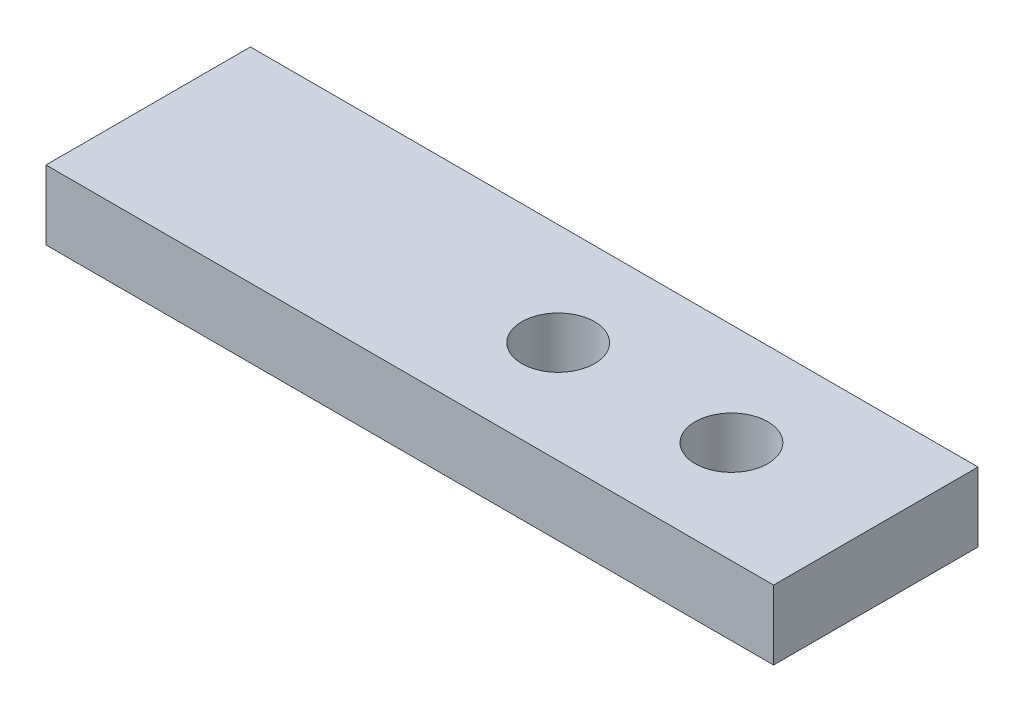
SolidWorks part; units mm, degrees
ref_plane "Front Plane" through (0, 0, 0) normal (0, 0, 1) x (1, 0, 0)
ref_plane "Top Plane" through (0, 0, 0) normal (0, 1, 0) x (1, 0, 0)
ref_plane "Right Plane" through (0, 0, 0) normal (1, 0, 0) x (0, 0, -1)
sketch "Sketch1" plane through (0, 0, 0) normal (0, 1, 0) x (1, 0, 0)
  line L0 (0, 0) -> (16.002, 0) construction
  line L1 (-16.002, 4.4958) -> (16.002, 4.4958)
  line L2 (-16.002, 4.4958) -> (-16.002, -4.4958)
  line L3 (-16.002, -4.4958) -> (16.002, -4.4958)
  line L4 (16.002, 4.4958) -> (16.002, -4.4958)
  line L5 (-16.002, 4.4958) -> (16.002, -4.4958) construction
  line L6 (-16.002, -4.4958) -> (16.002, 4.4958) construction
  circle A0 centre (9.652, 0) radius 1.6002
  circle A1 centre (2.032, 0) radius 1.6002
  point P0 (0, 0)
  dimension "D3" = 3.2004
  dimension "D4" = 3.2004
  dimension "D1" = 32.004
  dimension "D2" = 8.9916
  dimension "D5" = 7.62
  dimension "D6" = 6.35
extrude "Boss-Extrude1" add sketch "Sketch1" along normal blind 3.048
